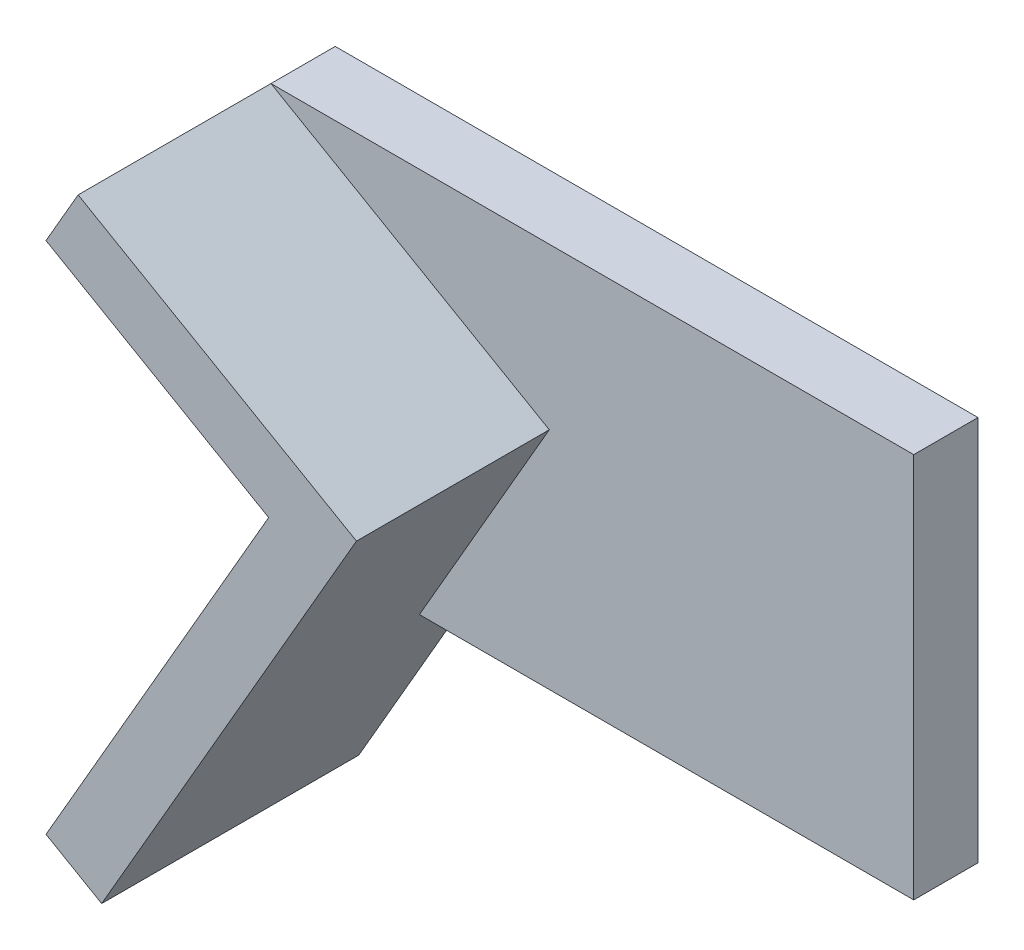
SolidWorks part; units mm, degrees
ref_plane "Front Plane" through (0, 0, 0) normal (0, 0, 1) x (1, 0, 0)
ref_plane "Top Plane" through (0, 0, 0) normal (0, 1, 0) x (1, 0, 0)
ref_plane "Right Plane" through (0, 0, 0) normal (1, 0, 0) x (0, 0, -1)
sketch "Sketch1" plane through (0, 0, 0) normal (0, 0, 1) x (1, 0, 0)
  line L0 (0, 0) -> (3.4641, 6)
  line L1 (3.4641, 6) -> (0, 8)
  line L2 (0, 0) -> (-6.4509, 0) construction
  line L3 (0, 8) -> (0, 0) construction
  line L4 (0.866, -0.5) -> (4.8301, 6.366)
  line L5 (4.8301, 6.366) -> (0.5, 8.866)
  line L6 (0, 0) -> (0.866, -0.5)
  line L7 (0, 8) -> (0.5, 8.866)
  dimension "D1" = 120
  dimension "D2" = 4
  dimension "D3" = 1
extrude "Boss-Extrude1" add sketch "Sketch1" along normal blind 4
sketch "Sketch2" plane through (0, 0, 0) normal (0, 0, -1) x (-1, 0, 0)
  line L0 (-0.5, 8.866) -> (-10.5, 8.866)
  line L2 (-10.5, 8.866) -> (-10.5, 2.866)
  line L3 (-10.5, 2.866) -> (-2.8094, 2.866)
  line L4 (-0.866, -0.5) -> (-4.8301, 6.366) construction
  line L5 (-2.8094, 2.866) -> (-4.8301, 6.366)
  line L6 (-4.8301, 6.366) -> (-0.5, 8.866)
  point P2 (-0.5, 8.866)
  point P8 (0, 0)
  dimension "D1" = 10
  dimension "D2" = 6
extrude "Boss-Extrude2" add sketch "Sketch2" against normal blind 1
